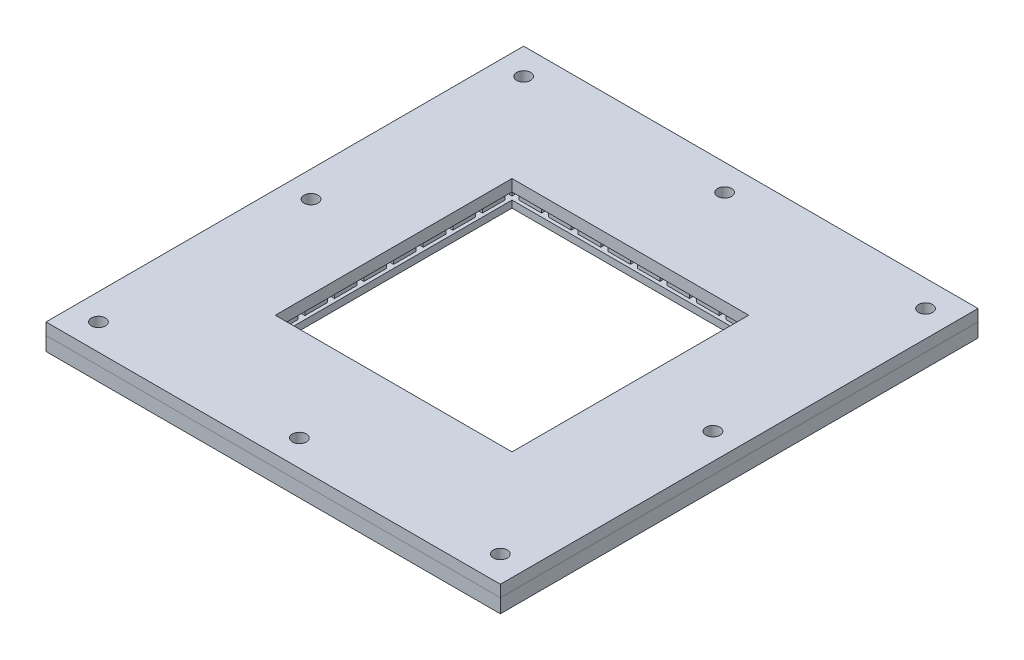
SolidWorks part; units mm, degrees
ref_plane "Front Plane" through (0, 0, 0) normal (0, 0, 1) x (1, 0, 0)
ref_plane "Top Plane" through (0, 0, 0) normal (0, 1, 0) x (1, 0, 0)
ref_plane "Right Plane" through (0, 0, 0) normal (1, 0, 0) x (0, 0, -1)
sketch "Sketch1" plane through (0, 0, 0) normal (0, 1, 0) x (1, 0, 0)
  line L1 (-97.5, 102.5) -> (97.5, 102.5)
  line L2 (-97.5, 102.5) -> (-97.5, -102.5)
  line L3 (-97.5, -102.5) -> (97.5, -102.5)
  line L4 (97.5, 102.5) -> (97.5, -102.5)
  line L5 (-50.8, 50.8) -> (50.8, 50.8)
  line L6 (-50.8, 50.8) -> (-50.8, -50.8)
  line L7 (-50.8, -50.8) -> (50.8, -50.8)
  line L8 (50.8, 50.8) -> (50.8, -50.8)
  point P4 (-97.5, 0)
  point P6 (0, 102.5)
  point P11 (0, 50.8)
  point P12 (-50.8, 0)
  dimension "D1" = 205
  dimension "D2" = 195
  dimension "D3" = 101.6
extrude "Boss-Extrude1" add sketch "Sketch1" along normal blind 6
sketch "Sketch2" plane through (0, 6, 0) normal (0, 1, 0) x (1, 0, 0)
  line L1 (-76.2, 77.7) -> (76.2, 77.7)
  line L2 (-76.2, 77.7) -> (-76.2, 74.7)
  line L3 (-76.2, 74.7) -> (76.2, 74.7)
  line L4 (76.2, 77.7) -> (76.2, 74.7)
  point P4 (0, 74.7)
  point P6 (-76.2, 76.2)
  dimension "D1" = 3
  dimension "D2" = 152.4
  dimension "D3" = 76.2
extrude "Cut-Extrude1" cut sketch "Sketch2" against normal blind 3
sketch "Sketch3" plane through (0, 6, 0) normal (0, 1, 0) x (1, 0, 0)
  line L0 (76.2, 74.7) -> (76.2, 77.7) construction
  line L1 (-77.7, 76.2) -> (-74.7, 76.2)
  line L2 (-77.7, 76.2) -> (-77.7, -76.2)
  line L3 (-77.7, -76.2) -> (-74.7, -76.2)
  line L4 (-74.7, 76.2) -> (-74.7, -76.2)
  line L5 (76.2, 77.7) -> (-76.2, 77.7) construction
  line L6 (-76.2, 77.7) -> (-76.2, 74.7) construction
  point P9 (-74.395, 75.4334)
  point P10 (-76.2, 76.2)
  point P13 (-76.2, 76.2)
extrude "Cut-Extrude2" cut sketch "Sketch3" against normal blind 3
pattern_linear "LPattern1" count 11 spacing 12.7 along (0, 0, 1) of "Cut-Extrude1"
pattern_linear "LPattern2" count 11 spacing 12.7 along (1, 0, 0) of "Cut-Extrude2"
mirror "Mirror1" about plane through (0, 0, 0) normal (0, 0, 1) of "LPattern1", "Cut-Extrude1"
mirror "Mirror2" about plane through (0, 0, 0) normal (1, 0, 0) of "LPattern2", "Cut-Extrude2"
sketch "Sketch4" plane through (0, 6, 0) normal (0, 1, 0) x (1, 0, 0)
  line L1 (-97.5, 102.5) -> (97.5, 102.5)
  line L2 (-97.5, 102.5) -> (-97.5, -102.5)
  line L3 (-97.5, -102.5) -> (97.5, -102.5)
  line L4 (97.5, 102.5) -> (97.5, -102.5)
  line L5 (-50.8, 50.8) -> (50.8, 50.8)
  line L6 (-50.8, 50.8) -> (-50.8, -50.8)
  line L7 (-50.8, -50.8) -> (50.8, -50.8)
  line L8 (50.8, 50.8) -> (50.8, -50.8)
extrude "Boss-Extrude2" add sketch "Sketch4" along normal blind 5 separate body
sketch "Sketch5" plane through (0, 11, 0) normal (0, 1, 0) x (1, 0, 0)
  line L0 (-97.5, 0) -> (-75, 0) construction
  line L1 (0, 102.5) -> (0, 80) construction
  line L2 (75, 0) -> (97.5, 0) construction
  line L3 (0, -80) -> (0, -102.5) construction
  line L4 (-97.5, 102.5) -> (-97.5, -102.5) construction
  line L5 (97.5, -102.5) -> (97.5, 102.5) construction
  line L6 (97.5, 102.5) -> (-97.5, 102.5) construction
  line L7 (-97.5, -102.5) -> (97.5, -102.5) construction
  circle A0 centre (-86.25, 91.25) radius 3
  circle A1 centre (0, 91.25) radius 3
  circle A2 centre (86.25, 91.25) radius 3
  circle A3 centre (-86.25, 0) radius 3
  circle A4 centre (86.25, 0) radius 3
  circle A5 centre (86.25, -91.25) radius 3
  circle A6 centre (0, -91.25) radius 3
  circle A7 centre (-86.25, -91.25) radius 3
  point P24 (0, 0)
  point P27 (0, 0)
  point P30 (0, 0)
  point P33 (0, 0)
  dimension "D1" = 6
  dimension "D2" = 22.5
extrude "Cut-Extrude3" cut sketch "Sketch5" against normal through all
equation "\"L\"= 6in'Length of wire mesh"
equation "\"D3@Sketch1\"=\"L\"-4*\"P\""
equation "\"D\"= 3mm'Wire diameter"
equation "\"D1@Boss-Extrude1\"=3mm+\"D\""
equation "\"P\"= 0.5in'Wire pitch"
equation "\"D1@Sketch2\"=\"D\""
equation "\"D2@Sketch2\"=\"L\""
equation "\"D3@Sketch2\"=\"L\"/2"
equation "\"D1@Cut-Extrude1\"=\"D\""
equation "\"D1@Cut-Extrude2\"=\"D\""
equation "\"D3@LPattern1\"=\"P\""
equation "\"D3@LPattern2\"=\"P\""
